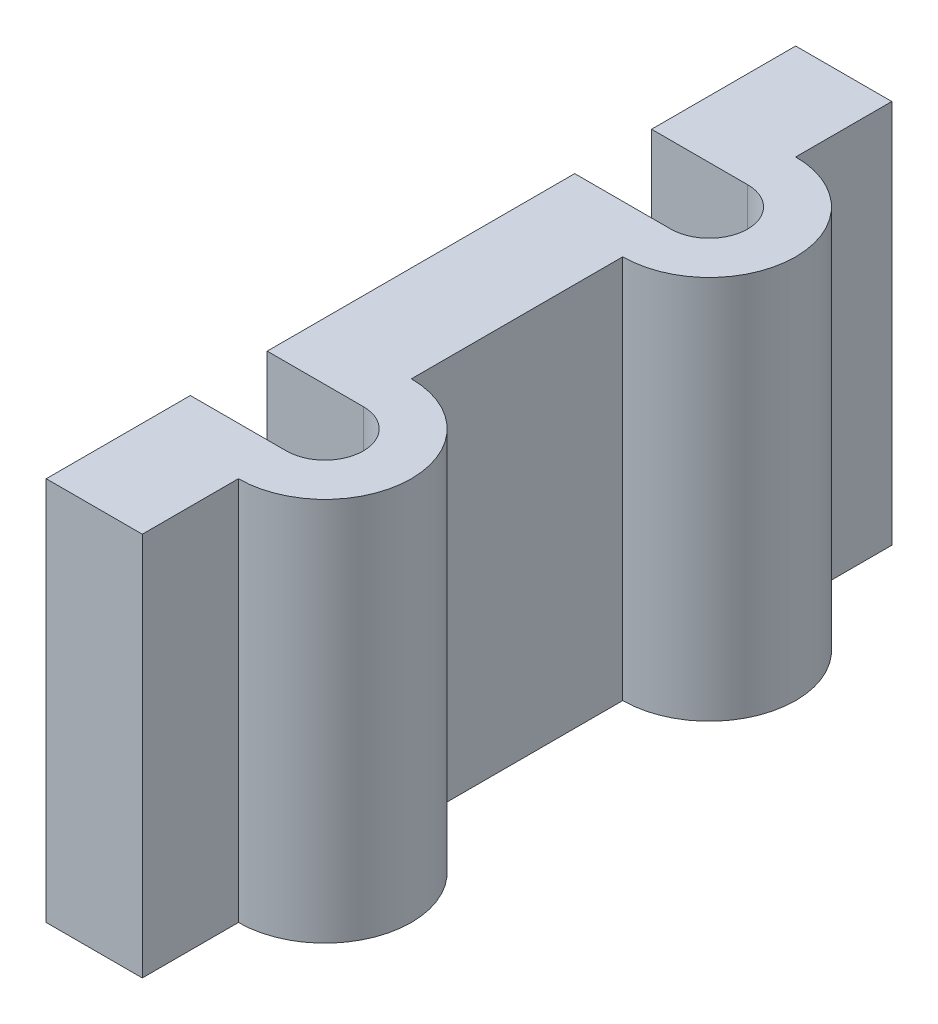
SolidWorks part; units mm, degrees
ref_plane "Front Plane" through (0, 0, 0) normal (0, 0, 1) x (1, 0, 0)
ref_plane "Top Plane" through (0, 0, 0) normal (0, 1, 0) x (1, 0, 0)
ref_plane "Right Plane" through (0, 0, 0) normal (1, 0, 0) x (0, 0, -1)
sketch "Sketch2" plane through (0, 0, 0) normal (0, 1, 0) x (1, 0, 0)
  line L0 (0, 0) -> (0, 15)
  line L1 (0, 0) -> (10, 0)
  line L2 (10, 0) -> (10, 10)
  line L3 (10, 28) -> (10, 50)
  line L4 (0, 39) -> (10, 39) construction
  line L7 (0, 15) -> (10, 15)
  line L8 (0, 23) -> (10, 23)
  line L9 (0, 23) -> (0, 55)
  line L10 (0, 55) -> (10, 55)
  line L11 (0, 63) -> (10, 63)
  line L12 (10, 78) -> (10, 68)
  line L13 (0, 78) -> (10, 78)
  line L14 (0, 78) -> (0, 63)
  arc A0 (10, 10) -> (10, 28) centre (10, 19) ccw
  arc A4 (10, 23) -> (10, 15) centre (10, 19) cw
  arc A5 (10, 55) -> (10, 63) centre (10, 59) ccw
  arc A6 (10, 68) -> (10, 50) centre (10, 59) cw
  point P12 (5, 15)
  point P19 (0, 0)
  dimension "D2" = 4
  dimension "D3" = 8
  dimension "D6" = 5
  dimension "D1" = 20
  dimension "D4" = 10
  dimension "D5" = 10
extrude "Boss-Extrude1" add sketch "Sketch2" along normal blind 40
